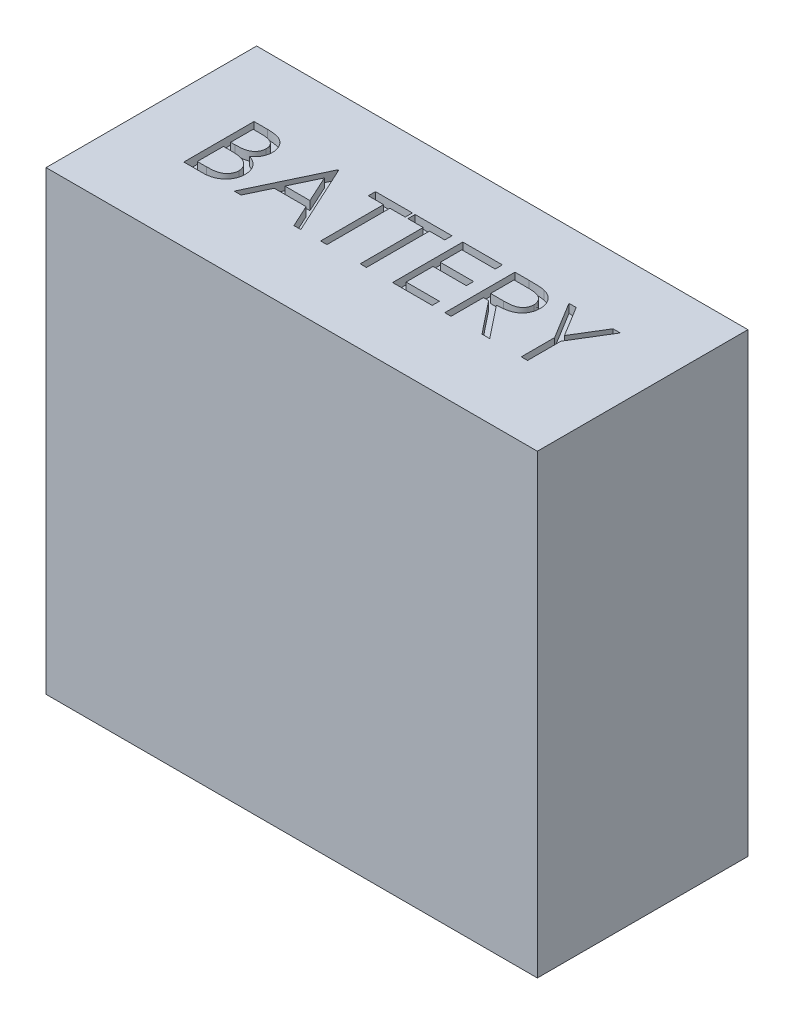
SolidWorks part; units mm, degrees
ref_plane "Front Plane" through (0, 0, 0) normal (0, 0, 1) x (1, 0, 0)
ref_plane "Top Plane" through (0, 0, 0) normal (0, 1, 0) x (1, 0, 0)
ref_plane "Right Plane" through (0, 0, 0) normal (1, 0, 0) x (0, 0, -1)
sketch "Sketch2" plane through (0, 0, 0) normal (0, 0, 1) x (1, 0, 0)
  line L1 (-88.9, 82.55) -> (88.9, 82.55)
  line L2 (-88.9, 82.55) -> (-88.9, -82.55)
  line L3 (-88.9, -82.55) -> (88.9, -82.55)
  line L4 (88.9, 82.55) -> (88.9, -82.55)
  line L5 (-88.9, 82.55) -> (88.9, -82.55) construction
  line L6 (-88.9, -82.55) -> (88.9, 82.55) construction
  point P0 (0, 0)
  dimension "D1" = 165.1
  dimension "D2" = 177.8
extrude "Boss-Extrude1" add sketch "Sketch2" along normal blind 76.2 contours L1 L4 L3 L2
sketch "Sketch3" plane through (0, 82.55, 0) normal (0, 1, 0) x (1, 0, 0)
  text T0 "BATTERY" font "Century Gothic" height 25.4
extrude "Cut-Extrude1" cut sketch "Sketch3" against normal blind 3.175
